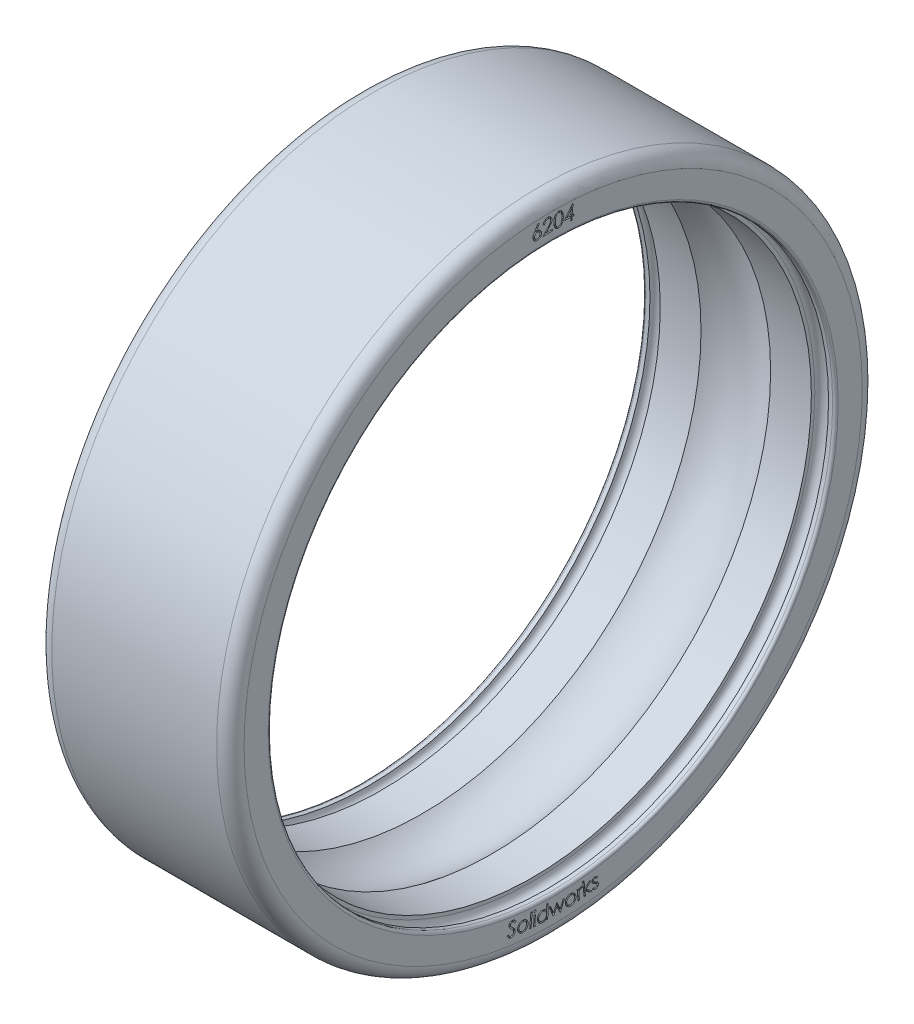
SolidWorks part; units mm, degrees
ref_plane "Front Plane" through (0, 0, 0) normal (0, 0, 1) x (1, 0, 0)
ref_plane "Top Plane" through (0, 0, 0) normal (0, 1, 0) x (1, 0, 0)
ref_plane "Right Plane" through (0, 0, 0) normal (1, 0, 0) x (0, 0, -1)
sketch "Sketch1" plane through (0, 0, 0) normal (0, 0, 1) x (1, 0, 0)
  line L0 (0, 10) -> (0, 0) construction
  line L1 (-6, 10) -> (6, 10) construction
  line L2 (0, 0) -> (-11.4383, 0) construction
  line L3 (5.5, 20.295) -> (5.5, 20.5463)
  line L4 (-7, 11) -> (-7, 14.15) construction
  line L5 (-5.5, 14.4) -> (-2.8566, 14.4) construction
  line L6 (7, 14.4) -> (7, 11) construction
  line L7 (-6, 23.5) -> (6, 23.5)
  line L8 (7, 22.5) -> (7, 20.7463)
  line L9 (5.5, 20.295) -> (2.534, 20.295)
  line L10 (-7, 20.7463) -> (-7, 22.5)
  line L11 (0, 17.2) -> (7, 17.2) construction
  line L12 (7, 17.2) -> (7, 20.295) construction
  line L13 (2.8566, 14.4) -> (7, 14.4) construction
  line L14 (-2.534, 20.295) -> (-5.5, 20.295)
  line L15 (7, 17.2) -> (7, 14.4) construction
  line L16 (-6.8, 20.5463) -> (-6.5, 20.5463)
  line L17 (6.5, 20.5463) -> (6.8, 20.5463)
  line L18 (5.5, 20.295) -> (7, 20.295) construction
  line L19 (-5.5, 20.295) -> (-5.5, 20.5463)
  line L20 (-6.5, 20.5463) -> (-5.5, 20.5463) construction
  line L21 (-6, 20.5463) -> (-5.5, 20.5463) construction
  line L22 (5.5, 20.5463) -> (6, 20.5463) construction
  line L23 (-5.5, 14.4) -> (-5.5, 14.15) construction
  line L24 (-5.5, 14.15) -> (-7, 14.15) construction
  line L25 (-5.5, 20.295) -> (-5.5, 14.4) construction
  arc A0 (6, 10) -> (7, 11) centre (6, 11) ccw construction
  arc A1 (-7, 11) -> (-6, 10) centre (-6, 11) ccw construction
  arc A2 (6, 23.5) -> (7, 22.5) centre (6, 22.5) cw
  arc A3 (-6, 23.5) -> (-7, 22.5) centre (-6, 22.5) ccw
  arc A4 (-2.8566, 14.4) -> (2.8566, 14.4) centre (0, 17.2) ccw construction
  arc A5 (2.534, 20.295) -> (-2.534, 20.295) centre (0, 17.2) ccw
  arc A8 (-6.5, 20.5463) -> (-5.5, 20.5463) centre (-6, 20.5463) cw
  arc A9 (5.5, 20.5463) -> (6.5, 20.5463) centre (6, 20.5463) cw
  arc A10 (-6.8, 20.5463) -> (-7, 20.7463) centre (-6.8, 20.7463) cw
  arc A11 (6.8, 20.5463) -> (7, 20.7463) centre (6.8, 20.7463) ccw
  point P37 (-7, 20.5463)
  point P40 (7, 20.5463)
  dimension "D6" = 1
  dimension "D7" = 8
  dimension "D10" = 0.5
  dimension "D11" = 4
  dimension "D15" = 0.2513
  dimension "D16" = 0.5
  dimension "D22" = 0.2
  dimension "D24" = 20.5463
  dimension "D2" = 10
  dimension "D3" = 14.4
  dimension "D4" = 20.295
  dimension "D5" = 23.5
  dimension "D8" = 3.095
  dimension "D9" = 2.8
  dimension "D12" = 7
  dimension "D13" = 0.2513
  dimension "D14" = 0.5
  dimension "D17" = 14
  dimension "D18" = 17.2
  dimension "D19" = 1.5
  dimension "D20" = 0.2513
  dimension "D21" = 0.5
  dimension "D23" = 1.5
  dimension "D25" = 0.25
  dimension "D26" = 14.15
revolve "Revolve1" add sketch "Sketch1" angle 360 about L2
sketch "Sketch2" plane through (0, 0, 0) normal (1, 0, 0) x (0, 0, -1)
  circle A0 centre (0, 0) radius 23.5 construction
  point P0 (0, -23.5)
  point P1 (0, 23.5)
  point P4 (-0.621, 23.4918)
  point P5 (0, 23.5)
  point P6 (0, 23.5)
  point P8 (0, 0)
sketch "Sketch3" plane through (7, 0, 0) normal (1, 0, 0) x (0, 0, -1)
  line L0 (0, 0) -> (0, 21.25) construction
  line L1 (0, 0) -> (0, -22) construction
  arc A0 (-7.987, 19.6919) -> (7.987, 19.6919) centre (0, 0) cw construction
  arc A1 (-11.631, -18.6741) -> (11.631, -18.6741) centre (0, 0) ccw construction
  text T0 "6204" font "Century Gothic" height 1
  text T1 "Solidworks" font "Century Gothic" height 1
  point P6 (0, 21.25)
  dimension "D1" = 21.25
  dimension "D2" = 22
extrude "Cut-Extrude1" cut sketch "Sketch3" against normal blind 0.1
sketch "Sketch4" plane through (-7, 0, 0) normal (-1, 0, 0) x (0, 0, 1)
  line L0 (0, 0) -> (-0.0869, -22) construction
  line L1 (0, 21.25) -> (0, 0) construction
  arc A0 (-8.686, 19.3937) -> (8.686, 19.3937) centre (0, 0) cw construction
  arc A1 (-7.6447, -20.6293) -> (7.4815, -20.689) centre (0, 0) ccw construction
  text T0 "6204" font "Century Gothic" height 1
  text T1 "Solidworks" font "Century Gothic" height 1
  dimension "D1" = 21.25
  dimension "D2" = 22
extrude "Cut-Extrude2" cut sketch "Sketch4" against normal blind 0.1
